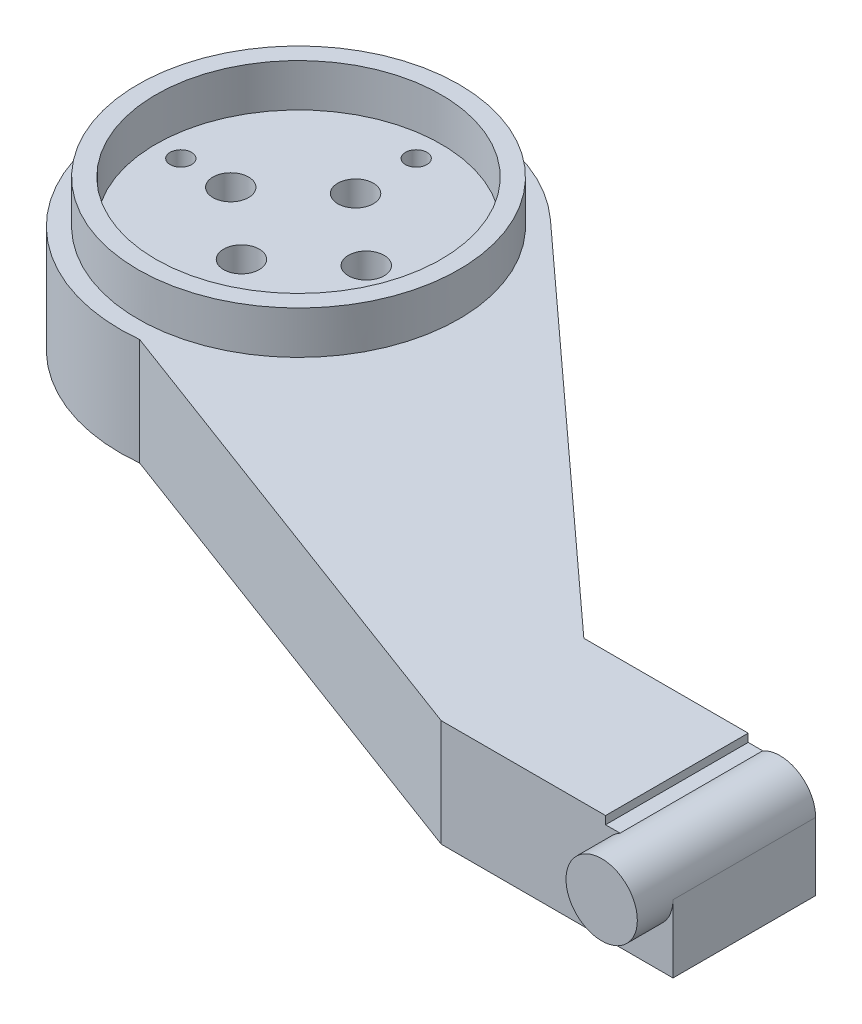
SolidWorks part; units mm, degrees
material "ABS"
ref_plane "前基準面" through (0, 0, 0) normal (0, 0, 1) x (1, 0, 0)
ref_plane "上基準面" through (0, 0, 0) normal (0, 1, 0) x (1, 0, 0)
ref_plane "右基準面" through (0, 0, 0) normal (1, 0, 0) x (0, 0, -1)
sketch "草圖1" plane through (0, 0, 0) normal (0, 1, 0) x (1, 0, 0)
  line L1 (-17.5, -10) -> (17.5, -10)
  line L2 (-17.5, -10) -> (-17.5, 10)
  line L3 (-17.5, 10) -> (17.5, 10)
  line L4 (17.5, -10) -> (17.5, 10)
  line L5 (-17.5, -10) -> (17.5, 10) construction
  line L6 (-17.5, 10) -> (17.5, -10) construction
  point P0 (0, 0)
  dimension "D1" = 35
  dimension "D2" = 20
extrude "填料-伸長1" add sketch "草圖1" along normal blind 10 and the other way blind 5
sketch "草圖17" plane through (0, 0, 10) normal (0, 0, 1) x (1, 0, 0)
  line L0 (17.5, -5) -> (17.5, 10) construction
  circle A1 centre (10, 4.5) radius 5
  dimension "D1" = 10
  dimension "D2" = 7.5
extrude "填料-伸長3" add sketch "草圖17" along normal blind 5
sketch "草圖7" plane through (0, 0, -10) normal (0, 0, 1) x (1, 0, 0)
  line L1 (17.5, 10) -> (17.5, -5) construction
  line L6 (13, 4.5) -> (49022, 4.5) construction
  circle A0 centre (10, 4.5) radius 3
  dimension "D1" = 6
  dimension "D2" = 7.5
extrude "除料-伸長7" cut sketch "草圖7" against normal mid plane 10
sketch "草圖12" plane through (0, 0, 0) normal (0, 0, 1) x (1, 0, 0)
  line L0 (15, 4.5) -> (15, -5)
  line L1 (15, -5) -> (17.5465, -5)
  line L2 (7.5817, 8.8763) -> (5.5465, 8.8763)
  line L4 (5.5465, 8.8763) -> (5.5465, 10.4978)
  line L5 (5.5465, 10.4978) -> (17.5465, 10.4978)
  line L6 (17.5465, 10.4978) -> (17.5465, -5)
  arc A0 (15, 4.5) -> (7.5817, 8.8763) centre (10, 4.5) ccw
  dimension "D1" = 10
  dimension "D2" = 12
extrude "除料-伸長12" cut sketch "草圖12" against normal through all both and the other way through all
sketch "草圖14" plane through (0, -5, 0) normal (0, 1, 0) x (1, 0, 0)
  line L0 (-17.5, 10) -> (-70.6546, 58.4725)
  line L1 (-84.9034, 15.1352) -> (-17.5, -10)
  line L2 (-17.5, 10) -> (-17.5, -10)
  arc A0 (-70.6546, 58.4725) -> (-84.9034, 15.1352) centre (-87.5, 40) ccw
  dimension "D1" = 25
  dimension "D2" = 70
  dimension "D3" = 50
extrude "填料-伸長2" add sketch "草圖14" along normal blind 15
sketch "草圖19" plane through (0, 10, 0) normal (0, 1, 0) x (1, 0, 0)
  circle A0 centre (-87.5, 40) radius 20
  circle A1 centre (-87.5, 40) radius 22.5
  dimension "D1" = 40
  dimension "D2" = 45
extrude "填料-伸長4" add sketch "草圖19" along normal blind 6
sketch "草圖20" plane through (0, 10, 0) normal (0, 1, 0) x (1, 0, 0)
  line L0 (-1087.5, 40) -> (48912.5, 40) construction
  line L1 (-87.5, -955.3026) -> (-87.5, 49044.6974) construction
  circle A0 centre (-87.5, 48) radius 2.5
  circle A1 centre (-87.5, 56.5) radius 1.5
  circle A2 centre (-97, 40) radius 2.5
  circle A3 centre (-104, 40) radius 1.5
  circle A4 centre (-87.5, 32) radius 2.5
  circle A5 centre (-87.5, 23.5) radius 1.5
  circle A6 centre (-71, 40) radius 1.5
  circle A7 centre (-78, 40) radius 2.5
  dimension "D1" = 3
  dimension "D2" = 5
  dimension "D3" = 33
  dimension "D4" = 33
  dimension "D5" = 16
  dimension "D6" = 19
extrude "除料-伸長16" cut sketch "草圖20" against normal blind 6
